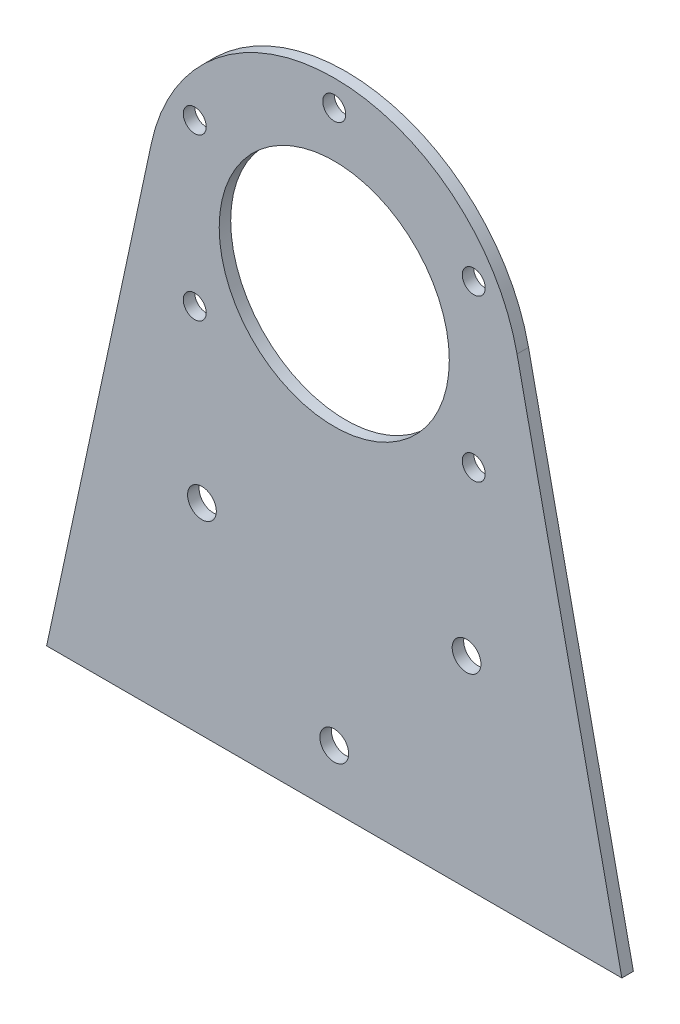
SolidWorks part; units mm, degrees
ref_plane "Front Plane" through (0, 0, 0) normal (0, 0, 1) x (1, 0, 0)
ref_plane "Top Plane" through (0, 0, 0) normal (0, 1, 0) x (1, 0, 0)
ref_plane "Right Plane" through (0, 0, 0) normal (1, 0, 0) x (0, 0, -1)
sketch "Sketch1" plane through (0, 0, 0) normal (0, 0, 1) x (1, 0, 0)
  line L3 (-50, -78) -> (50, -78)
  line L4 (0, 0) -> (0, -28) construction
  line L6 (-50, -78) -> (-31.7749, 6.8269)
  line L7 (50, -78) -> (31.7749, 6.8269)
  line L9 (0, -28) -> (-70.4492, -28) construction
  line L10 (0, -65.5) -> (0, -97.2613) construction
  arc A0 (31.7749, 6.8269) -> (-31.7749, 6.8269) centre (0, 0) ccw
  circle A1 centre (0, 0) radius 20
  circle A2 centre (0, 28) radius 2
  circle A3 centre (24.2487, 14) radius 2
  circle A4 centre (24.2487, -14) radius 2
  circle A6 centre (-24.2487, -14) radius 2
  circle A7 centre (-24.2487, 14) radius 2
  circle A8 centre (0, -28) radius 2 [skipped]
  circle A9 centre (0, -68) radius 2.5
  circle A10 centre (23, -43) radius 2.5
  circle A11 centre (-23, -43) radius 2.5
  point P19 (0, 0)
  point P25 (0, 0)
  dimension "D1" = 40
  dimension "D2" = 65
  dimension "D5" = 4
  dimension "D10" = 5
  dimension "D11" = 5
  dimension "D12" = 5
  dimension "D3" = 28
  dimension "D6" = 25
  dimension "D7" = 100
  dimension "D8" = 50
  dimension "D9" = 23
  dimension "D13" = 50
  dimension "D14" = 10
  dimension "D15" = 28
  dimension "D16" = 23
  dimension "D4" = 6
extrude "Boss-Extrude1" add sketch "Sketch1" along normal blind 2
